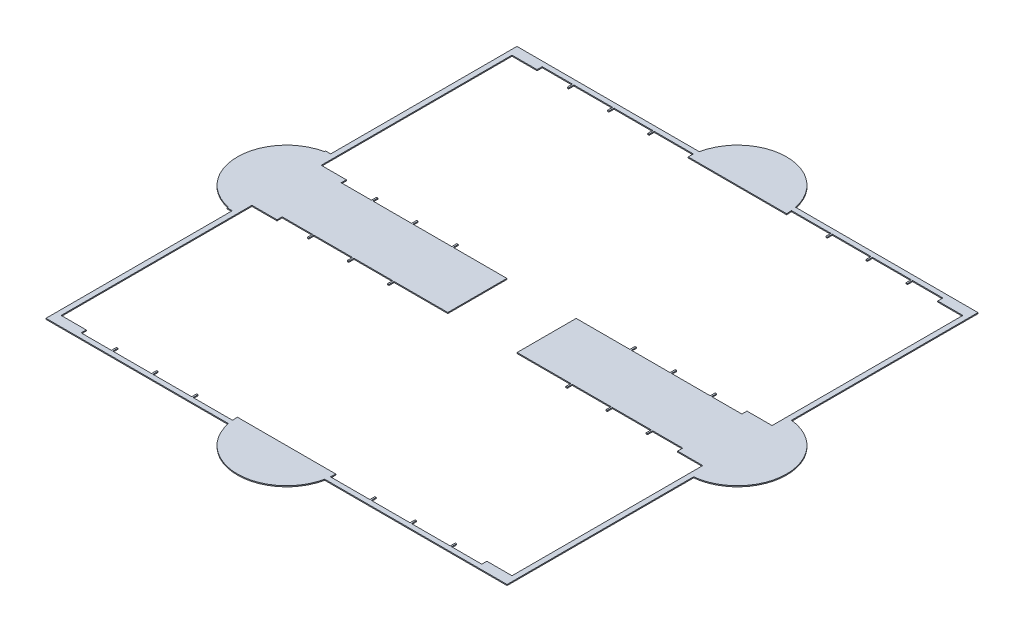
SolidWorks part; units mm, degrees
ref_plane "Front Plane" through (0, 0, 0) normal (0, 0, 1) x (1, 0, 0)
ref_plane "Top Plane" through (0, 0, 0) normal (0, 1, 0) x (1, 0, 0)
ref_plane "Right Plane" through (0, 0, 0) normal (1, 0, 0) x (0, 0, -1)
sketch "Sketch1" plane through (0, 0, 0) normal (0, 1, 0) x (1, 0, 0)
  line L0 (-55, 0) -> (55, 0) construction
  line L1 (-11.225, -11.225) -> (11.225, -11.225)
  line L2 (-11.225, -11.225) -> (-11.225, 11.225)
  line L3 (-11.225, 11.225) -> (11.225, 11.225)
  line L4 (11.225, -11.225) -> (11.225, 11.225)
  line L5 (-11.225, -11.225) -> (11.225, 11.225) construction
  line L6 (-11.225, 11.225) -> (11.225, -11.225) construction
  line L7 (-11.225, 11.225) -> (-1.725, 11.225)
  line L8 (-11.225, 11.225) -> (-11.225, 1.725)
  line L9 (-11.225, 1.725) -> (-1.725, 1.725)
  line L11 (-2.45, 11.73) -> (2.45, 11.73)
  line L12 (-11.225, -1.725) -> (-1.725, -1.725)
  line L13 (0, -55) -> (0, 55) construction
  line L14 (-11.73, -2.45) -> (-11.98, -2.45)
  line L15 (11.225, -1.725) -> (1.725, -1.725)
  line L16 (-11.73, -2.45) -> (-11.73, 2.45)
  line L17 (11.225, 1.725) -> (1.725, 1.725)
  line L18 (-1.725, 1.47) -> (-11.225, 1.47)
  line L19 (11.48, -11.48) -> (-11.48, -11.48)
  line L20 (11.48, -11.48) -> (11.48, 11.48)
  line L21 (11.48, 11.48) -> (-11.48, 11.48)
  line L22 (-11.48, -11.48) -> (-11.48, 11.48)
  line L23 (11.48, -11.48) -> (-11.48, 11.48) construction
  line L24 (11.48, 11.48) -> (-11.48, -11.48) construction
  line L25 (11.225, -1.47) -> (1.725, -1.47)
  line L26 (11.225, -1.47) -> (11.225, 1.47)
  line L27 (11.225, 1.47) -> (1.725, 1.47)
  line L28 (-11.225, -1.47) -> (-11.225, 1.47)
  line L29 (11.225, -1.47) -> (-11.225, 1.47) construction
  line L30 (11.225, 1.47) -> (-11.225, -1.47) construction
  line L31 (-1.225, -11.225) -> (1.225, -11.225)
  line L33 (-1.225, 11.225) -> (1.225, 11.225)
  line L35 (-11.73, 2.45) -> (-11.98, 2.45)
  line L36 (-11.98, -2.45) -> (-11.98, 2.45)
  line L38 (-1.725, -1.47) -> (-11.225, -1.47)
  line L40 (-11.48, 0) -> (-15.585, 0) construction
  line L41 (1.725, 1.725) -> (-1.725, 1.725)
  line L42 (1.725, 1.725) -> (1.725, -1.725)
  line L43 (1.725, -1.725) -> (-1.725, -1.725)
  line L44 (-1.725, 1.725) -> (-1.725, -1.725)
  line L45 (1.725, 1.725) -> (-1.725, -1.725) construction
  line L46 (1.725, -1.725) -> (-1.725, 1.725) construction
  line L47 (-11.48, -2.45) -> (-11.73, -2.45)
  line L48 (-11.48, 1.45) -> (-11.73, 1.45)
  line L49 (-11.48, 1.45) -> (-11.48, 2.45)
  line L50 (-11.48, 2.45) -> (-11.73, 2.45)
  line L51 (-11.73, 1.45) -> (-11.73, 2.45)
  line L52 (-11.73, -1.45) -> (-11.73, -2.45)
  line L53 (-11.48, -1.45) -> (-11.73, -1.45)
  line L54 (-11.48, -1.45) -> (-11.48, -2.45)
  line L55 (1.45, 11.48) -> (2.45, 11.48)
  line L56 (1.45, 11.48) -> (1.45, 11.73)
  line L57 (1.45, 11.73) -> (2.45, 11.73)
  line L58 (2.45, 11.48) -> (2.45, 11.73)
  line L59 (-2.45, 11.48) -> (-2.45, 11.73)
  line L60 (-1.45, 11.73) -> (-2.45, 11.73)
  line L61 (-1.45, 11.48) -> (-1.45, 11.73)
  line L62 (-1.45, 11.48) -> (-2.45, 11.48)
  line L63 (11.48, -1.45) -> (11.48, -2.45)
  line L64 (11.48, -1.45) -> (11.73, -1.45)
  line L65 (11.73, -1.45) -> (11.73, -2.45)
  line L66 (11.48, -2.45) -> (11.73, -2.45)
  line L67 (11.48, 2.45) -> (11.73, 2.45)
  line L68 (11.73, 1.45) -> (11.73, 2.45)
  line L69 (11.48, 1.45) -> (11.73, 1.45)
  line L70 (11.48, 1.45) -> (11.48, 2.45)
  line L71 (-1.45, -11.48) -> (-2.45, -11.48)
  line L72 (-1.45, -11.48) -> (-1.45, -11.73)
  line L73 (-1.45, -11.73) -> (-2.45, -11.73)
  line L74 (-2.45, -11.48) -> (-2.45, -11.73)
  line L75 (2.45, -11.48) -> (2.45, -11.73)
  line L76 (1.45, -11.73) -> (2.45, -11.73)
  line L77 (1.45, -11.48) -> (1.45, -11.73)
  line L78 (1.45, -11.48) -> (2.45, -11.48)
  line L79 (-2.45, 11.73) -> (-2.45, 11.98)
  line L80 (-2.45, 11.98) -> (2.45, 11.98)
  line L81 (2.45, 11.73) -> (2.45, 11.98)
  line L82 (11.73, 2.45) -> (11.73, -2.45)
  line L83 (11.73, 2.45) -> (11.98, 2.45)
  line L84 (11.98, 2.45) -> (11.98, -2.45)
  line L85 (11.73, -2.45) -> (11.98, -2.45)
  line L86 (2.45, -11.73) -> (-2.45, -11.73)
  line L87 (2.45, -11.73) -> (2.45, -11.98)
  line L88 (2.45, -11.98) -> (-2.45, -11.98)
  line L89 (-2.45, -11.73) -> (-2.45, -11.98)
  circle A0 centre (0, 0) radius 0.975
  point P0 (0, 0)
  point P77 (0, 0)
  point P89 (0, 0)
  dimension "D3" = 1.95
  dimension "D1" = 22.45
  dimension "D2" = 9.5
  dimension "D4" = 0.255
  dimension "D5" = 0.255
  dimension "D6" = 0.25
  dimension "D7" = 0.255
  dimension "D8" = 0.25
  dimension "D9" = 1.45
  dimension "D10" = 1
  dimension "D11" = 4
  dimension "D12" = 4
extrude "Boss-Extrude5" add sketch "Sketch1" along normal blind 0.05 contours L22 L19 L20 L21 L4 L1 L2 L3 | L44 L38 L2 L12 | L44 L9 L2 L18 | L41 L44 L43 L42 A0 | L17 L42 L27 L4 | L25 L42 L15 L4 | L47 L52 L53 L54 | L49 L48 L51 L50
sketch "Sketch2" plane through (0, 0.05, 0) normal (0, 1, 0) x (1, 0, 0)
  line L0 (-6.435, 1.225) -> (-6.435, 11.225) construction
  line L2 (-11.225, 11.225) -> (11.225, 11.225) construction
  line L3 (-11.225, 1.725) -> (11.225, 1.725) construction
  line L4 (-6.4, 1.225) -> (-6.47, 1.225)
  line L5 (-6.4, 1.225) -> (-6.4, 1.725)
  line L6 (-6.4, 1.725) -> (-6.47, 1.725)
  line L7 (-6.47, 1.225) -> (-6.47, 1.725)
  line L8 (-8.47, 1.725) -> (-8.4, 1.725)
  line L9 (-4.4, 1.225) -> (-4.47, 1.225)
  line L10 (-4.4, 1.225) -> (-4.4, 1.725)
  line L11 (-4.4, 1.725) -> (-4.47, 1.725)
  line L12 (-4.47, 1.225) -> (-4.47, 1.725)
  line L13 (-8.4, 1.225) -> (-8.4, 1.725)
  line L14 (-8.47, 1.225) -> (-8.4, 1.225)
  line L15 (-8.47, 1.225) -> (-8.47, 1.725)
  line L16 (-11.225, 6.475) -> (11.225, 6.475) construction
  line L17 (-11.225, 1.725) -> (-11.225, 11.225) construction
  line L18 (11.225, 1.725) -> (11.225, 11.225) construction
  line L19 (-8.4, 1.725) -> (-6.47, 1.725) construction
  line L20 (-4.4, 11.225) -> (-4.47, 11.225)
  line L21 (-4.47, 11.725) -> (-4.47, 11.225)
  line L22 (-4.4, 11.725) -> (-4.47, 11.725)
  line L23 (-4.4, 11.725) -> (-4.4, 11.225)
  line L24 (-6.4, 11.225) -> (-6.47, 11.225)
  line L25 (-6.47, 11.725) -> (-6.47, 11.225)
  line L26 (-6.4, 11.725) -> (-6.47, 11.725)
  line L27 (-6.4, 11.725) -> (-6.4, 11.225)
  line L28 (-8.47, 11.725) -> (-8.47, 11.225)
  line L29 (-8.47, 11.725) -> (-8.4, 11.725)
  line L30 (-8.4, 11.725) -> (-8.4, 11.225)
  line L31 (-8.47, 11.225) -> (-8.4, 11.225)
  line L32 (0, -55) -> (0, 55) construction
  line L33 (4.4, 1.725) -> (4.47, 1.725)
  line L34 (4.47, 1.225) -> (4.47, 1.725)
  line L35 (4.4, 1.225) -> (4.47, 1.225)
  line L36 (4.4, 1.225) -> (4.4, 1.725)
  line L37 (6.4, 1.725) -> (6.47, 1.725)
  line L38 (6.47, 1.225) -> (6.47, 1.725)
  line L39 (6.4, 1.225) -> (6.47, 1.225)
  line L40 (6.4, 1.225) -> (6.4, 1.725)
  line L41 (8.47, 1.225) -> (8.47, 1.725)
  line L42 (8.47, 1.225) -> (8.4, 1.225)
  line L43 (8.4, 1.225) -> (8.4, 1.725)
  line L44 (8.47, 1.725) -> (8.4, 1.725)
  line L45 (4.4, 11.725) -> (4.4, 11.225)
  line L46 (4.4, 11.725) -> (4.47, 11.725)
  line L47 (4.47, 11.725) -> (4.47, 11.225)
  line L48 (4.4, 11.225) -> (4.47, 11.225)
  line L49 (6.4, 11.725) -> (6.4, 11.225)
  line L50 (6.4, 11.725) -> (6.47, 11.725)
  line L51 (6.47, 11.725) -> (6.47, 11.225)
  line L52 (6.4, 11.225) -> (6.47, 11.225)
  line L53 (8.47, 11.725) -> (8.4, 11.725)
  line L54 (8.4, 11.725) -> (8.4, 11.225)
  line L55 (8.47, 11.225) -> (8.4, 11.225)
  line L56 (8.47, 11.725) -> (8.47, 11.225)
  line L57 (-55, 0) -> (55, 0) construction
  line L58 (-8.47, -11.725) -> (-8.4, -11.725)
  line L59 (-8.4, -11.725) -> (-8.4, -11.225)
  line L60 (-8.47, -11.225) -> (-8.4, -11.225)
  line L61 (-8.47, -11.725) -> (-8.47, -11.225)
  line L62 (-6.4, -11.725) -> (-6.4, -11.225)
  line L63 (-6.4, -11.725) -> (-6.47, -11.725)
  line L64 (-6.47, -11.725) -> (-6.47, -11.225)
  line L65 (-6.4, -11.225) -> (-6.47, -11.225)
  line L66 (-4.4, -11.725) -> (-4.4, -11.225)
  line L67 (-4.4, -11.725) -> (-4.47, -11.725)
  line L68 (-4.47, -11.725) -> (-4.47, -11.225)
  line L69 (-4.4, -11.225) -> (-4.47, -11.225)
  line L70 (4.4, -11.725) -> (4.47, -11.725)
  line L71 (4.47, -11.725) -> (4.47, -11.225)
  line L72 (4.4, -11.225) -> (4.47, -11.225)
  line L73 (4.4, -11.725) -> (4.4, -11.225)
  line L74 (6.4, -11.725) -> (6.47, -11.725)
  line L75 (6.47, -11.725) -> (6.47, -11.225)
  line L76 (6.4, -11.225) -> (6.47, -11.225)
  line L77 (6.4, -11.725) -> (6.4, -11.225)
  line L78 (8.47, -11.725) -> (8.47, -11.225)
  line L79 (8.47, -11.225) -> (8.4, -11.225)
  line L80 (8.4, -11.725) -> (8.4, -11.225)
  line L81 (8.47, -11.725) -> (8.4, -11.725)
  line L82 (8.47, -1.225) -> (8.4, -1.225)
  line L83 (8.4, -1.225) -> (8.4, -1.725)
  line L84 (8.47, -1.725) -> (8.4, -1.725)
  line L85 (8.47, -1.225) -> (8.47, -1.725)
  line L86 (6.4, -1.225) -> (6.4, -1.725)
  line L87 (6.4, -1.225) -> (6.47, -1.225)
  line L88 (6.47, -1.225) -> (6.47, -1.725)
  line L89 (6.4, -1.725) -> (6.47, -1.725)
  line L90 (4.4, -1.225) -> (4.4, -1.725)
  line L91 (4.4, -1.225) -> (4.47, -1.225)
  line L92 (4.47, -1.225) -> (4.47, -1.725)
  line L93 (4.4, -1.725) -> (4.47, -1.725)
  line L94 (-4.4, -1.725) -> (-4.47, -1.725)
  line L95 (-4.47, -1.225) -> (-4.47, -1.725)
  line L96 (-4.4, -1.225) -> (-4.47, -1.225)
  line L97 (-4.4, -1.225) -> (-4.4, -1.725)
  line L98 (-6.4, -1.725) -> (-6.47, -1.725)
  line L99 (-6.47, -1.225) -> (-6.47, -1.725)
  line L100 (-6.4, -1.225) -> (-6.47, -1.225)
  line L101 (-6.4, -1.225) -> (-6.4, -1.725)
  line L102 (-8.47, -1.225) -> (-8.47, -1.725)
  line L103 (-8.47, -1.225) -> (-8.4, -1.225)
  line L104 (-8.4, -1.225) -> (-8.4, -1.725)
  line L105 (-8.47, -1.725) -> (-8.4, -1.725)
  point P12 (-6.435, 1.225)
  dimension "D1" = 0.07
  dimension "D2" = 2
  dimension "D3" = 0.5
extrude "Cut-Extrude1" cut sketch "Sketch2" against normal blind 10 contours L28 L31 L30 L29 | L24 L25 L26 L27 | L20 L21 L22 L23 | L45 L48 L47 L46 | L49 L52 L51 L50 | L53 L54 L55 L56 | L41 L44 L43 L42 | L37 L38 L39 L40 | L33 L34 L35 L36 | L90 L93 L92 L91 | L86 L89 L88 L87 | L82 L83 L84 L85 | L78 L79 L80 L81 | L74 L75 L76 L77 | L70 L71 L72 L73 | L66 L69 L68 L67 | L62 L65 L64 L63 | L58 L59 L60 L61 | L102 L105 L104 L103 | L98 L99 L100 L101 | L94 L95 L96 L97 | L10 L9 L12 L11 | L5 L4 L7 L6 | L8 L13 L14 L15
sketch "Sketch3" plane through (0, 0.05, 0) normal (0, 1, 0) x (1, 0, 0)
  line L0 (-8.47, -11.48) -> (-11.48, -11.48) construction
  line L1 (-9.975, -11.48) -> (-11.73, -11.48)
  line L2 (-9.975, -11.48) -> (-9.975, 11.48)
  line L3 (-9.975, 11.48) -> (-11.73, 11.48)
  line L4 (-11.73, -11.48) -> (-11.73, 11.48)
  line L5 (-8.47, 11.48) -> (-11.48, 11.48) construction
  line L6 (-11.73, -1.45) -> (-11.73, -2.45) construction
  line L7 (0, 0) -> (0, 11.48) construction
  line L8 (4.4, 11.48) -> (-4.4, 11.48) construction
  line L9 (-11.225, 1.725) -> (-8.47, 1.725) construction
  line L10 (2.2862, 11.48) -> (-2.2862, 11.48)
  line L11 (0, 11.48) -> (0, 1.725)
  line L12 (2.2862, 1.725) -> (-2.2862, 1.725)
  line L13 (-2.2862, 11.48) -> (-2.2862, 1.725)
  line L14 (-0.0275, 0) -> (0.0275, 0) construction
  line L15 (2.2862, -1.725) -> (-2.2862, -1.725)
  line L16 (-2.2862, -11.48) -> (-2.2862, -1.725)
  line L17 (2.2862, -11.48) -> (-2.2862, -11.48)
  line L18 (0, -11.48) -> (0, -1.725)
  line L19 (0, -0.0275) -> (0, 0.0275) construction
  line L20 (2.2862, -11.48) -> (2.2862, -1.725)
  line L21 (2.2862, 11.48) -> (2.2862, 1.725)
  line L22 (9.975, 11.48) -> (11.73, 11.48)
  line L23 (11.73, -11.48) -> (11.73, 11.48)
  line L24 (9.975, -11.48) -> (11.73, -11.48)
  line L25 (9.975, -11.48) -> (9.975, 11.48)
  line L27 (-9.975, 11.48) -> (-2.2862, 11.48)
  line L28 (-9.975, 11.48) -> (-9.975, -11.48)
  line L29 (-9.975, -11.48) -> (-2.2862, -11.48)
  line L30 (-2.2862, 11.48) -> (-2.2862, -11.48)
  line L31 (2.2862, 11.48) -> (9.975, 11.48)
  line L32 (2.2862, 11.48) -> (2.2862, -11.48)
  line L33 (2.2862, -11.48) -> (9.975, -11.48)
  line L34 (9.975, 11.48) -> (9.975, -11.48)
  line L35 (-2.2862, 1.725) -> (2.2862, 1.725)
  line L36 (-2.2862, 1.725) -> (-2.2862, -1.725)
  line L37 (-2.2862, -1.725) -> (2.2862, -1.725)
  line L38 (2.2862, 1.725) -> (2.2862, -1.725)
extrude "Cut-Extrude3" cut sketch "Sketch3" against normal blind 10
sketch "Sketch5" plane through (0, 0.05, 0) normal (0, 1, 0) x (1, 0, 0)
  line L0 (-11.225, -1.47) -> (-11.225, 1.47) construction
  line L1 (-11.225, 2.45) -> (-11.225, -2.45)
  line L2 (-9.975, -1.47) -> (-11.225, -1.47) construction
  line L3 (-11.225, 1.47) -> (-8.47, 1.47)
  line L4 (-11.225, 1.47) -> (-11.225, -1.47)
  line L5 (-11.225, -1.47) -> (-8.47, -1.47)
  line L6 (-1.725, 1.47) -> (-1.725, -1.47)
  line L7 (-0.0275, 0) -> (0.0275, 0) construction
  line L9 (-8.47, 1.47) -> (-8.47, 1.725)
  line L10 (-8.47, 1.725) -> (-8.4, 1.725)
  line L11 (-8.4, 1.47) -> (-8.4, 1.725)
  line L13 (-6.47, 1.47) -> (-6.47, 1.725)
  line L14 (-6.47, 1.725) -> (-6.4, 1.725)
  line L15 (-6.4, 1.47) -> (-6.4, 1.725)
  line L17 (-4.47, 1.47) -> (-4.47, 1.725)
  line L18 (-4.47, 1.725) -> (-4.4, 1.725)
  line L19 (-4.4, 1.47) -> (-4.4, 1.725)
  line L20 (-4.47, -1.725) -> (-4.4, -1.725)
  line L21 (-4.4, -1.47) -> (-4.4, -1.725)
  line L23 (-4.47, -1.47) -> (-4.47, -1.725)
  line L24 (-6.47, -1.725) -> (-6.4, -1.725)
  line L25 (-6.4, -1.47) -> (-6.4, -1.725)
  line L27 (-6.47, -1.47) -> (-6.47, -1.725)
  line L28 (-8.47, -1.725) -> (-8.4, -1.725)
  line L29 (-8.4, -1.47) -> (-8.4, -1.725)
  line L31 (-8.47, -1.47) -> (-8.47, -1.725)
  line L32 (-8.4, -1.47) -> (-6.47, -1.47)
  line L33 (-6.4, -1.47) -> (-4.47, -1.47)
  line L34 (-4.4, -1.47) -> (-1.725, -1.47)
  line L35 (-4.4, 1.47) -> (-1.725, 1.47)
  line L36 (-6.4, 1.47) -> (-4.47, 1.47)
  line L37 (-8.4, 1.47) -> (-6.47, 1.47)
  line L38 (2.45, 11.225) -> (-2.45, 11.225)
  line L39 (11.225, -2.45) -> (11.225, 2.45)
  line L40 (-2.45, -11.225) -> (2.45, -11.225)
  line L41 (0, -0.0275) -> (0, 0.0275) construction
  line L42 (11.225, 1.47) -> (11.225, -1.47)
  line L43 (11.225, -1.47) -> (8.47, -1.47)
  line L44 (8.47, -1.47) -> (8.47, -1.725)
  line L45 (8.47, -1.725) -> (8.4, -1.725)
  line L46 (8.4, -1.47) -> (8.4, -1.725)
  line L47 (8.4, -1.47) -> (6.47, -1.47)
  line L48 (6.47, -1.47) -> (6.47, -1.725)
  line L49 (6.47, -1.725) -> (6.4, -1.725)
  line L50 (6.4, -1.47) -> (6.4, -1.725)
  line L51 (6.4, -1.47) -> (4.47, -1.47)
  line L52 (4.47, -1.47) -> (4.47, -1.725)
  line L53 (4.47, -1.725) -> (4.4, -1.725)
  line L54 (4.4, -1.47) -> (4.4, -1.725)
  line L55 (4.4, -1.47) -> (1.725, -1.47)
  line L56 (1.725, 1.47) -> (1.725, -1.47)
  line L57 (4.4, 1.47) -> (1.725, 1.47)
  line L58 (4.4, 1.47) -> (4.4, 1.725)
  line L59 (4.47, 1.725) -> (4.4, 1.725)
  line L60 (4.47, 1.47) -> (4.47, 1.725)
  line L61 (6.4, 1.47) -> (4.47, 1.47)
  line L62 (6.4, 1.47) -> (6.4, 1.725)
  line L63 (6.47, 1.725) -> (6.4, 1.725)
  line L64 (6.47, 1.47) -> (6.47, 1.725)
  line L65 (8.4, 1.47) -> (6.47, 1.47)
  line L66 (8.4, 1.47) -> (8.4, 1.725)
  line L67 (8.47, 1.725) -> (8.4, 1.725)
  line L68 (8.47, 1.47) -> (8.47, 1.725)
  line L69 (11.225, 1.47) -> (8.47, 1.47)
  line L70 (-8.4, -11.48) -> (-6.47, -11.48)
  line L71 (-11.48, -11.48) -> (-8.47, -11.48)
  line L72 (-11.48, -11.48) -> (-11.48, -11.7249)
  line L73 (-11.48, -11.7249) -> (-2.3985, -11.7249)
  line L76 (-8.47, -11.48) -> (-8.47, -11.225)
  line L77 (-8.47, -11.225) -> (-8.4, -11.225)
  line L78 (-8.4, -11.48) -> (-8.4, -11.225)
  line L80 (-6.47, -11.48) -> (-6.47, -11.225)
  line L81 (-6.47, -11.225) -> (-6.4, -11.225)
  line L82 (-6.4, -11.48) -> (-6.4, -11.225)
  line L84 (-4.47, -11.48) -> (-4.47, -11.225)
  line L85 (-4.47, -11.225) -> (-4.4, -11.225)
  line L86 (-4.4, -11.48) -> (-4.4, -11.225)
  line L87 (-6.4, -11.48) -> (-4.47, -11.48)
  line L88 (-4.4, -11.48) -> (-2.4367, -11.48)
  line L89 (-4.4, 11.48) -> (-2.4367, 11.48)
  line L90 (-6.4, 11.48) -> (-4.47, 11.48)
  line L91 (-4.4, 11.48) -> (-4.4, 11.225)
  line L92 (-4.47, 11.225) -> (-4.4, 11.225)
  line L93 (-4.47, 11.48) -> (-4.47, 11.225)
  line L94 (-6.4, 11.48) -> (-6.4, 11.225)
  line L95 (-6.47, 11.225) -> (-6.4, 11.225)
  line L96 (-6.47, 11.48) -> (-6.47, 11.225)
  line L97 (-8.4, 11.48) -> (-8.4, 11.225)
  line L98 (-8.47, 11.225) -> (-8.4, 11.225)
  line L99 (-8.47, 11.48) -> (-8.47, 11.225)
  line L100 (-11.48, 11.7249) -> (-2.3985, 11.7249)
  line L101 (-11.48, 11.48) -> (-11.48, 11.7249)
  line L102 (-11.48, 11.48) -> (-8.47, 11.48)
  line L103 (-8.4, 11.48) -> (-6.47, 11.48)
  line L104 (8.4, 11.48) -> (6.47, 11.48)
  line L105 (11.48, 11.48) -> (8.47, 11.48)
  line L106 (11.48, 11.48) -> (11.48, 11.7249)
  line L107 (11.48, 11.7249) -> (2.3985, 11.7249)
  line L108 (8.47, 11.48) -> (8.47, 11.225)
  line L109 (8.47, 11.225) -> (8.4, 11.225)
  line L110 (8.4, 11.48) -> (8.4, 11.225)
  line L111 (6.47, 11.48) -> (6.47, 11.225)
  line L112 (6.47, 11.225) -> (6.4, 11.225)
  line L113 (6.4, 11.48) -> (6.4, 11.225)
  line L114 (4.47, 11.48) -> (4.47, 11.225)
  line L115 (4.47, 11.225) -> (4.4, 11.225)
  line L116 (4.4, 11.48) -> (4.4, 11.225)
  line L117 (6.4, 11.48) -> (4.47, 11.48)
  line L118 (4.4, 11.48) -> (2.4367, 11.48)
  line L119 (4.4, -11.48) -> (2.4367, -11.48)
  line L120 (6.4, -11.48) -> (4.47, -11.48)
  line L121 (4.4, -11.48) -> (4.4, -11.225)
  line L122 (4.47, -11.225) -> (4.4, -11.225)
  line L123 (4.47, -11.48) -> (4.47, -11.225)
  line L124 (6.4, -11.48) -> (6.4, -11.225)
  line L125 (6.47, -11.225) -> (6.4, -11.225)
  line L126 (6.47, -11.48) -> (6.47, -11.225)
  line L127 (8.4, -11.48) -> (8.4, -11.225)
  line L128 (8.47, -11.225) -> (8.4, -11.225)
  line L129 (8.47, -11.48) -> (8.47, -11.225)
  line L130 (11.48, -11.7249) -> (2.3985, -11.7249)
  line L131 (11.48, -11.48) -> (11.48, -11.7249)
  line L132 (11.48, -11.48) -> (8.47, -11.48)
  line L133 (8.4, -11.48) -> (6.47, -11.48)
  arc A0 (-11.225, 2.45) -> (-11.225, -2.45) centre (-11.225, 0) ccw
  arc A1 (2.45, 11.225) -> (-2.45, 11.225) centre (0, 11.225) ccw
  arc A2 (11.225, -2.45) -> (11.225, 2.45) centre (11.225, 0) ccw
  arc A3 (-2.45, -11.225) -> (2.45, -11.225) centre (0, -11.225) ccw
  point P50 (0, 0)
  line M7 (-11.48, -11.48) -> (-9.975, -11.48)
  line M13 (-9.975, -1.47) -> (-11.225, -1.47)
  line M14 (-11.225, -1.47) -> (-11.225, 1.47)
  line M15 (-11.225, 1.47) -> (-9.975, 1.47)
  line M21 (-9.975, 11.48) -> (-11.48, 11.48)
  line M24 (-11.73, 2.45) -> (-11.73, 1.45)
  line M25 (-11.73, 1.45) -> (-11.48, 1.45)
  line M26 (-11.48, 1.45) -> (-11.48, -1.45)
  line M27 (-11.48, -1.45) -> (-11.73, -1.45)
  line M28 (-11.73, -1.45) -> (-11.73, -2.45)
  dimension "D1" = 9.5
  dimension "D2" = 0.07
  dimension "D3" = 2.755
  dimension "D4" = 0.255
  dimension "D5" = 1.93
  dimension "D6" = 1.93
extrude "Boss-Extrude7" add sketch "Sketch5" against normal up to surface (0.05 mm away) contours A0 M24 M28 M27 M26 M25 | L6 L3 L5 M15 M14 M13 | L3 L11 L10 L9 | L3 L15 L14 L13 | L38 A1 | L39 L69 L68 L67 L66 L65 L64 L63 L62 L61 L60 L59 L58 L57 L56 L55 L54 L53 L52 L51 L50 L49 L48 L47 L46 L45 L44 L43 | L39 A2 | L40 A3 | A3 L88 L86 L85 L84 L87 L82 L81 L80 L70 L78 L77 L76 L71 L72 L73 M7 | A3 L130 L131 L132 L129 L128 L127 L133 L126 L125 L124 L120 L123 L122 L121 L119 | A1 L100 L101 L102 L99 L98 L97 L103 L96 L95 L94 L90 L93 L92 L91 L89 M21 | A1 L118 L116 L115 L114 L117 L113 L112 L111 L104 L110 L109 L108 L105 L106 L107
